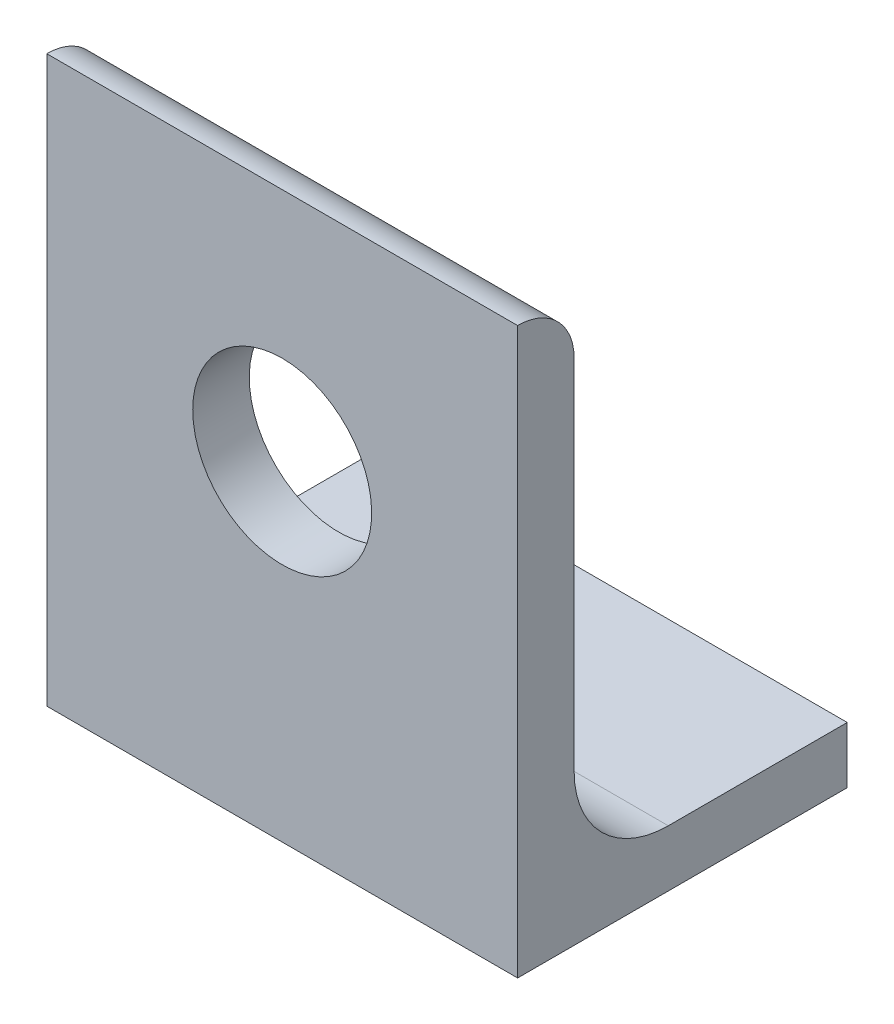
SolidWorks part; units mm, degrees
material "AISI 1020"
ref_plane "Front Plane" through (0, 0, 0) normal (0, 0, 1) x (1, 0, 0)
ref_plane "Top Plane" through (0, 0, 0) normal (0, 1, 0) x (1, 0, 0)
ref_plane "Right Plane" through (0, 0, 0) normal (1, 0, 0) x (0, 0, -1)
sketch "Sketch1" plane through (0, 0, 0) normal (0, 1, 0) x (1, 0, 0)
  line L0 (-25, 0) -> (0, 0)
  point P4 (-12.5, 0)
  dimension "D1" = 25
other "L angle (equal) 30X30X3(2)"
ref_plane "Plane1" through (-25, 0, 0) normal (1, 0, 0) x (0, 0, -1)
sketch "Sketch19" plane through (-25, 0, 0) normal (1, 0, 0) x (0, 0, -1)
  line L0 (0, 30) -> (0, 0)
  line L2 (3, 27) -> (3, 8)
  line L3 (8, 3) -> (27, 3)
  line L5 (30, 0) -> (0, 0)
  arc A0 (3, 27) -> (0, 30) centre (0, 27) ccw
  arc A1 (30, 0) -> (27, 3) centre (27, 0) ccw
  arc A2 (8, 3) -> (3, 8) centre (8, 8) cw
  point P8 (0, 15)
  point P9 (15, 0)
  point P10 (0, 0)
  dimension "Radius_2" = 3
  dimension "Radius_1" = 5
  dimension "V_leg" = 30
  dimension "H_leg" = 30
  dimension "thickness" = 3
sketch "Sketch12" plane through (0, 0, -3) normal (0, 0, -1) x (-1, 0, 0)
  line L0 (0, 8) -> (0, 27) construction
  circle A0 centre (12.5, 17.5) radius 4.25
  point P4 (0, 17.5)
  dimension "D1" = 8.5
  dimension "D2" = 12.5
sketch "Sketch15" plane through (0, 0, 0) normal (0, -1, 0) x (1, 0, 0)
  line L1 (-25, -17.5) -> (0, -17.5)
  line L2 (-25, -17.5) -> (-25, -30)
  line L3 (-25, -30) -> (0, -30)
  line L4 (0, -17.5) -> (0, -30)
  line L6 (-25, 0) -> (-25, -30) construction
  dimension "D1" = 12.5
hole_wizard "Ø9.5 (9.5) Diameter Hole1" positions "Sketch20" profile "Sketch21" hole size "Ø9.5" standard "ANSI Metric"
sketch "Sketch20" plane through (0, 0, -3) normal (0, 0, -1) x (-1, 0, 0)
  point P0 (12.5, 17.5)
sketch "Sketch21" plane through (-12.5, 17.5, -3) normal (1, 0, 0) x (0, 1, 0)
  line L0 (0, 0) -> (0, 20.8541)
  line L1 (0, 20.8541) -> (4.75, 18)
  line L2 (4.75, 18) -> (4.75, 0)
  line L5 (4.75, 0) -> (0, 0)
  line L10 (0, 20.8541) -> (-4.75, 18) construction
  line L11 (0, -6.35) -> (0, 107.95) construction
  dimension "Hole Dia." = 9.5
  dimension "Hole Depth" = 18
  dimension "Drill Angle" = 118
extrude "Cut-Extrude1" cut sketch "Sketch15" against normal up to next
